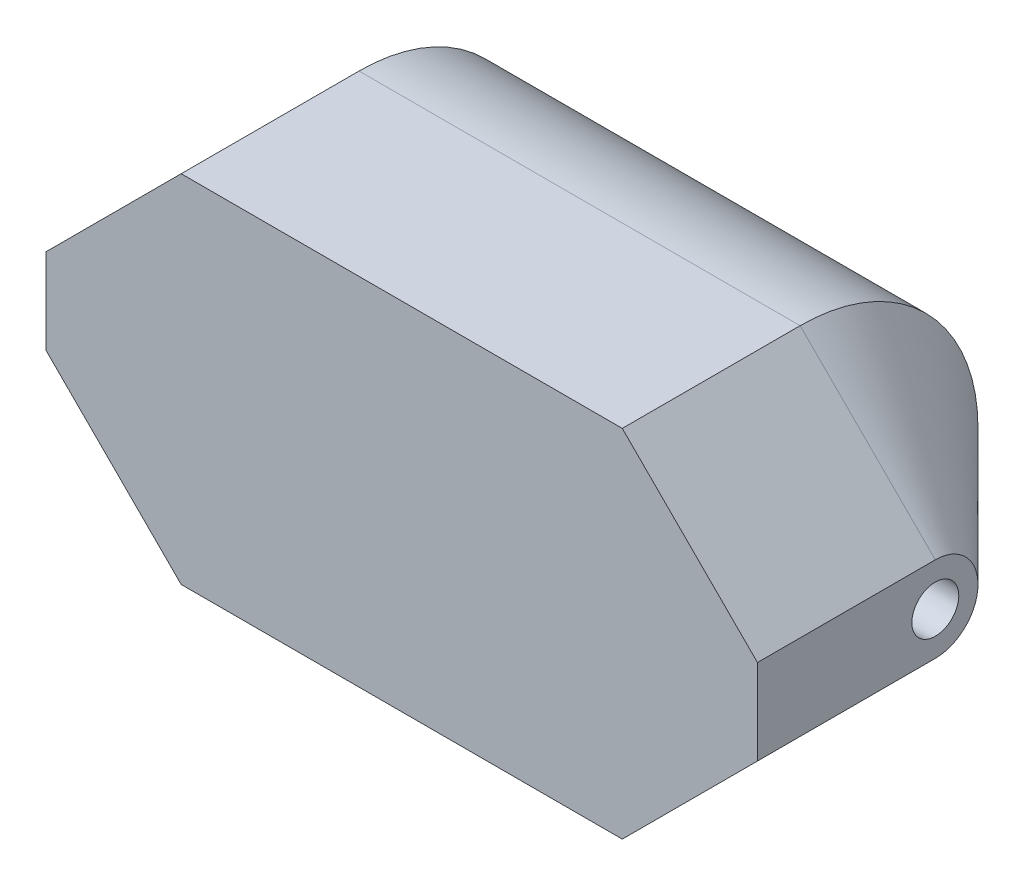
SolidWorks part; units mm, degrees
ref_plane "Front Plane" through (0, 0, 0) normal (0, 0, 1) x (1, 0, 0)
ref_plane "Top Plane" through (0, 0, 0) normal (0, 1, 0) x (1, 0, 0)
ref_plane "Right Plane" through (0, 0, 0) normal (1, 0, 0) x (0, 0, -1)
sketch "Sketch1" plane through (0, 0, 0) normal (1, 0, 0) x (0, 0, -1)
  line L0 (0, 12.5) -> (-12.5, 12.5)
  line L1 (-12.5, 12.5) -> (-12.5, -12.5)
  line L2 (-12.5, -12.5) -> (0, -12.5)
  arc A0 (0, -12.5) -> (0, 12.5) centre (0, 0) ccw
  circle A1 centre (0, 0) radius 1.65
  dimension "D1" = 12.5
  dimension "D2" = 3.3
extrude "Boss-Extrude1" add sketch "Sketch1" along normal blind 50 contours A1 | A0 L0 L1 L2
chamfer "Chamfer1" distance 9.5 angle 45 6 edges at (50, -12.5, 6.25) (50, 12.5, 6.25) (50, 0, -12.5) (0, -12.5, 6.25) (0, 12.5, 6.25) (0, 0, -12.5)
